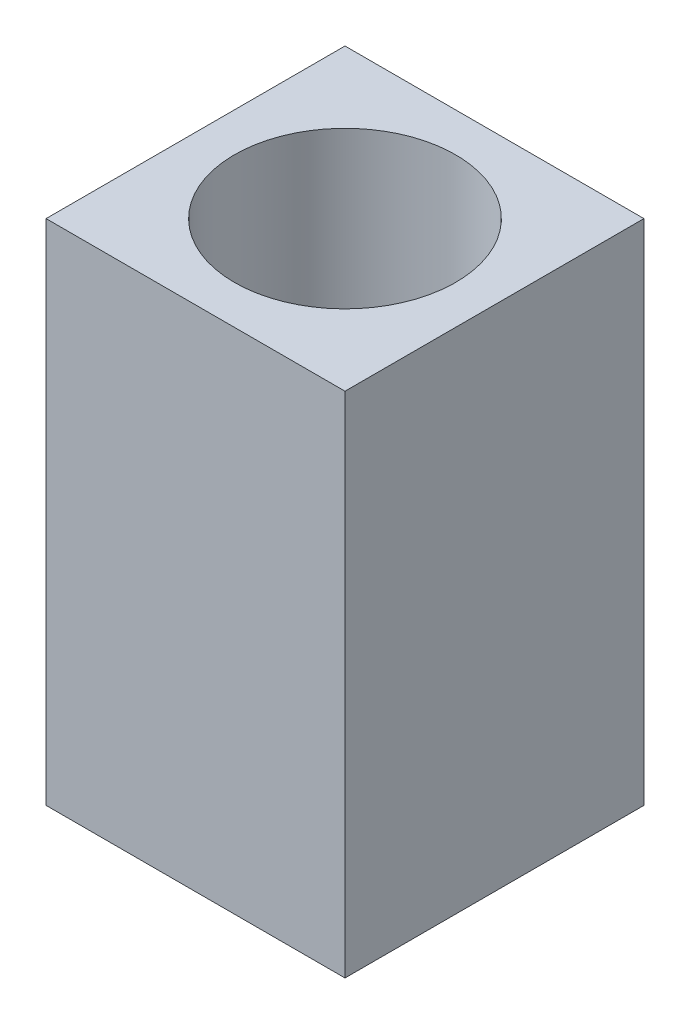
SolidWorks part; units mm, degrees
ref_plane "Спереди" through (0, 0, 0) normal (0, 0, 1) x (1, 0, 0)
ref_plane "Сверху" through (0, 0, 0) normal (0, 1, 0) x (1, 0, 0)
ref_plane "Справа" through (0, 0, 0) normal (1, 0, 0) x (0, 0, -1)
sketch "Sketch1" plane through (0, 0, 0) normal (0, 1, 0) x (1, 0, 0)
  line L0 (0, 0) -> (0, 10)
  line L5 (0, 10) -> (10, 10)
  line L6 (0, 0) -> (10, 0)
  line L7 (10, 0) -> (10, 10)
extrude "Boss-Extrude1" add sketch "Sketch1" along normal blind 17
sketch "Sketch2" plane through (0, 17, 0) normal (0, 1, 0) x (1, 0, 0)
  line L0 (0, 0) -> (10, 10)
  circle A0 centre (5, 5) radius 3.7
extrude "Cut-Extrude1" cut sketch "Sketch2" against normal blind 17 contours L0 A0 | L0 A0
